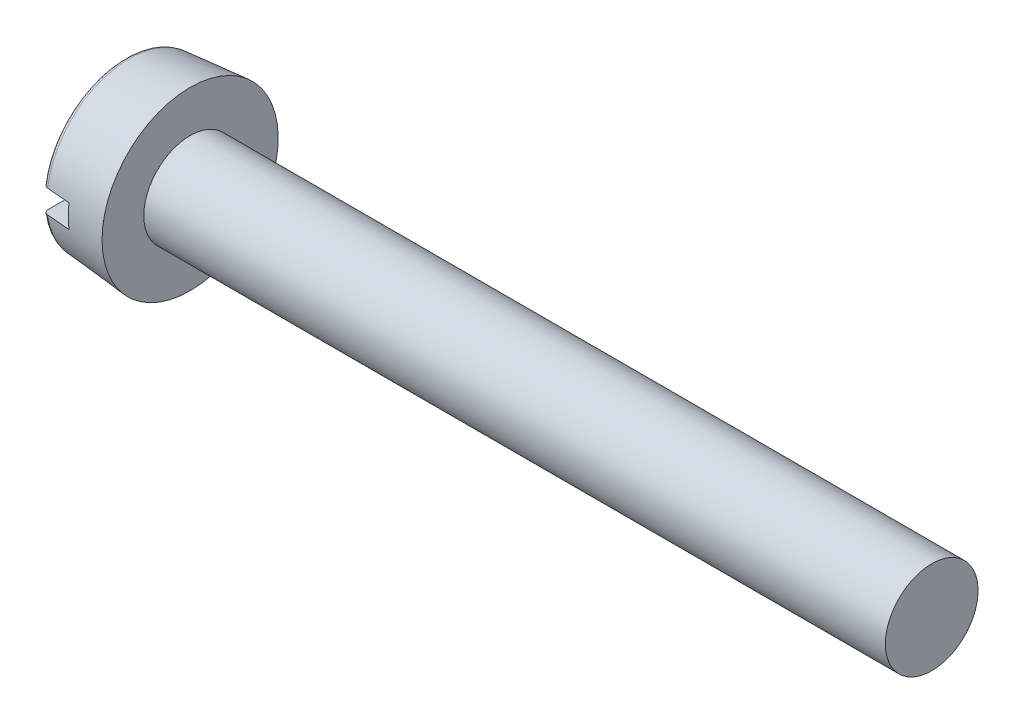
SolidWorks part; units mm, degrees
ref_plane "Plane1" through (0, 0, 0) normal (0, 0, 1) x (1, 0, 0)
ref_plane "Plane2" through (0, 0, 0) normal (0, 1, 0) x (1, 0, 0)
ref_plane "Plane3" through (0, 0, 0) normal (1, 0, 0) x (0, 0, -1)
sketch "BodySke" plane through (0, 0, 0) normal (0, 0, 1) x (1, 0, 0)
  line L0 (1.4, 1) -> (1.4, 1.9)
  line L1 (0, 0) -> (0, 1.7775)
  line L2 (-25.4, 0) -> (127, 0) construction
  line L3 (17.4, 0) -> (0, 0)
  line L4 (1.4, 1) -> (17.4, 1)
  line L5 (17.4, 1) -> (17.4, 0)
  line L6 (0, 1.7775) -> (1.4, 1.9)
  line L9 (1.8, 2.5875) -> (1.8, -6.9375) construction
  line L10 (1.4, 6.35) -> (1.4, -3.175) construction
  dimension "Length" = 16
  dimension "Head_ht" = 1.4
  dimension "Advance" = 0.4
  dimension "Thread_nom" = 16
  dimension "Head_dia" = 3.8
  dimension "Head_side_angle" = 5
  dimension "Diameter" = 2
revolve "Base-Revolve" add sketch "BodySke"
cosmetic thread "ThreadCosmetic" [suppressed]
fillet "Fillet1" [suppressed] radius 0.1
fillet "Fillet2" radius 0.1 1 edges at (0, 0, 1.7775)
sketch "Sketch2" plane through (0, 0, 0) normal (1, 0, 0) x (0, 0, -1)
  line L0 (1.9, -0.25) -> (-1.9, -0.25)
  line L1 (1.9, -0.25) -> (1.9, 0.25)
  line L2 (-1.9, 0.25) -> (1.9, 0.25)
  line L3 (-1.9, 0.25) -> (-1.9, -0.25)
  dimension "D1" = 3.8
  dimension "Slot_width" = 0.5
  dimension "D2" = 1.9
  dimension "D3" = 0.25
extrude "Slot" cut sketch "Sketch2" along normal blind 0.6
sketch "ThdSchSke" plane through (0, 0, 0) normal (0, 0, 1) x (1, 0, 0)
  line L0 (2.2, -0.774) -> (2.0418, -1)
  line L1 (2.2, -0.774) -> (2.3582, -1)
  line L2 (2.3582, -1) -> (2.3582, -1.25)
  line L3 (-3.175, 0) -> (5.1513, 0) construction
  line L5 (2.3582, -1.25) -> (2.0418, -1.25)
  line L6 (2.0418, -1.25) -> (2.0418, -1)
  dimension "Diameter" = 2
  dimension "SideAngle" = 55
  dimension "VeeAngle" = 70
  dimension "Thread_minor" = 1.548
  dimension "Overcut" = 2.5
  dimension "Start" = 2.2
revolve "ThreadSchematic" [suppressed] cut sketch "ThdSchSke" angle 360 about L3
pattern_linear "ThdSchPat" [suppressed]
equation "\"D1@Sketch2\" = \"Head_dia@BodySke\""
equation "\"D2@Sketch2\" = \"D1@Sketch2\" / 2"
equation "\"D3@Sketch2\" = \"Slot_width@Sketch2\" / 2"
equation "\"Thread_length@ThreadCosmetic\" = ((sgn( (\"Length@BodySke\" - \"Advance@BodySke\" * 2.0 ) - \"Thread_nom@BodySke\" )-1)*( (\"Length@BodySke\" - \"Advance@BodySke\"  * 2.0) - \"Thread_nom@BodySke\" ))/-2+ \"Thread_nom@BodySke\""
equation "\"Thread_minor@ThdSchSke\" = \"Thread_minor@ThreadCosmetic\""
equation "\"Diameter@ThdSchSke\" = \"Diameter@BodySke\""
equation "\"Overcut@ThdSchSke\" = \"Diameter@BodySke\" * 1.25"
equation "\"Start@ThdSchSke\" = \"Head_ht@BodySke\" + \"Length@BodySke\" - \"Thread_length@ThreadCosmetic\"  '---Non-countersunk---"
equation "\"Num_threads@ThdSchPat\" = int( \"Thread_length@ThreadCosmetic\" / \"Advance@BodySke\" + 0.999 )  + 1"
equation "\"Advance@ThdSchPat\" = \"Thread_length@ThreadCosmetic\" /  (\"Num_threads@ThdSchPat\" - 1) 'relax it"
